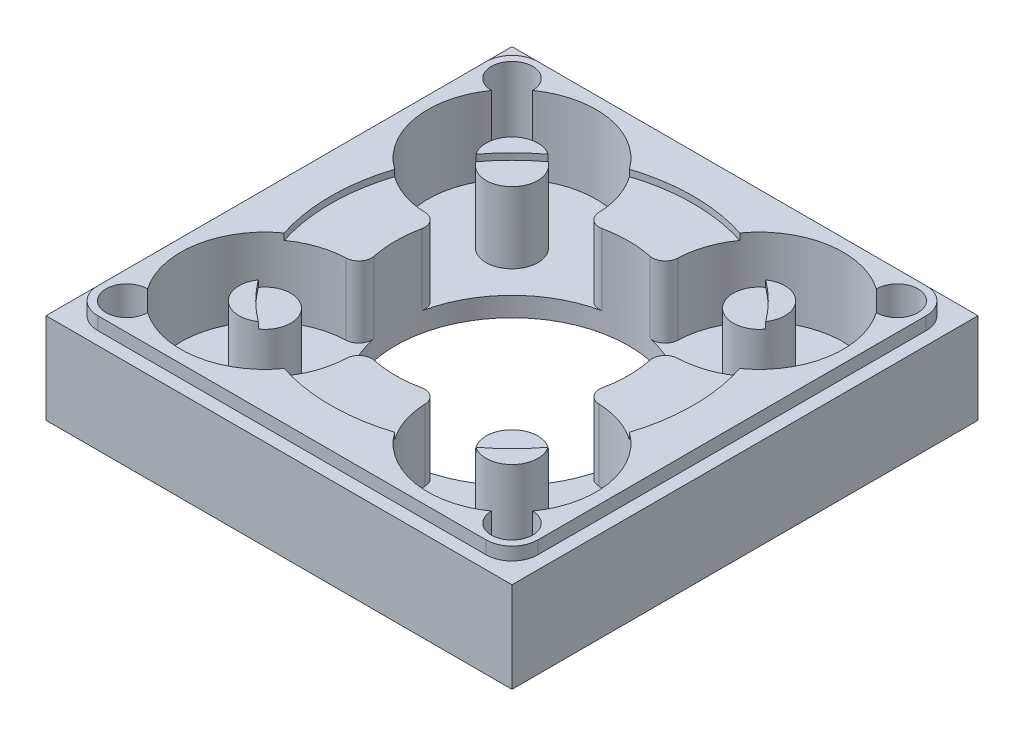
SolidWorks part; units mm, degrees
material "6061 Alloy"
ref_plane "Front Plane" through (0, 0, 0) normal (0, 0, 1) x (1, 0, 0)
ref_plane "Top Plane" through (0, 0, 0) normal (0, 1, 0) x (1, 0, 0)
ref_plane "Right Plane" through (0, 0, 0) normal (1, 0, 0) x (0, 0, -1)
sketch "Sketch1" plane through (0, 0, 0) normal (0, 1, 0) x (1, 0, 0)
  line L1 (-28.575, -28.575) -> (28.575, -28.575)
  line L2 (-28.575, -28.575) -> (-28.575, 28.575)
  line L3 (-28.575, 28.575) -> (28.575, 28.575)
  line L4 (28.575, -28.575) -> (28.575, 28.575)
  line L5 (-28.575, -28.575) -> (28.575, 28.575) construction
  line L6 (-28.575, 28.575) -> (28.575, -28.575) construction
  circle A0 centre (0, 0) radius 14.2875
  point P0 (0, 0)
  dimension "D2" = 28.575
  dimension "D1" = 57.15
extrude "Stock" add sketch "Sketch1" along normal blind 12.7
sketch "Sketch6" plane through (0, 0, 0) normal (0, -1, 0) x (1, 0, 0)
  line L1 (23.622, -23.622) -> (-23.622, -23.622) construction
  line L2 (23.622, -23.622) -> (23.622, 23.622) construction
  line L3 (23.622, 23.622) -> (-23.622, 23.622) construction
  line L4 (-23.622, -23.622) -> (-23.622, 23.622) construction
  line L5 (23.622, -23.622) -> (-23.622, 23.622) construction
  line L6 (23.622, 23.622) -> (-23.622, -23.622) construction
  circle A0 centre (-23.622, 23.622) radius 2.54
  circle A1 centre (23.622, 23.622) radius 2.54
  circle A2 centre (23.622, -23.622) radius 2.54
  circle A3 centre (-23.622, -23.622) radius 2.54
  point P0 (0, 0)
  dimension "D2" = 5.08
  dimension "D1" = 47.244
extrude "Mount Holes" cut sketch "Sketch6" against normal through all
sketch "Sketch2" plane through (0, 12.7, 0) normal (0, 1, 0) x (1, 0, 0)
  line L1 (-23.8125, -26.9875) -> (23.8125, -26.9875)
  line L2 (-26.9875, -23.8125) -> (-26.9875, 23.8125)
  line L3 (-23.8125, 26.9875) -> (23.8125, 26.9875)
  line L4 (26.9875, -23.8125) -> (26.9875, 23.8125)
  line L5 (-26.9875, -26.9875) -> (26.9875, 26.9875) construction
  line L6 (-26.9875, 26.9875) -> (26.9875, -26.9875) construction
  line L7 (28.575, 28.575) -> (-28.575, 28.575)
  line L8 (28.575, 28.575) -> (28.575, -28.575)
  line L9 (28.575, -28.575) -> (-28.575, -28.575)
  line L10 (-28.575, 28.575) -> (-28.575, -28.575)
  line L11 (28.575, 28.575) -> (-28.575, -28.575) construction
  line L12 (28.575, -28.575) -> (-28.575, 28.575) construction
  arc A0 (23.8125, 26.9875) -> (26.9875, 23.8125) centre (23.8125, 23.8125) cw
  arc A1 (23.8125, -26.9875) -> (26.9875, -23.8125) centre (23.8125, -23.8125) ccw
  arc A2 (-23.8125, -26.9875) -> (-26.9875, -23.8125) centre (-23.8125, -23.8125) cw
  arc A3 (-26.9875, 23.8125) -> (-23.8125, 26.9875) centre (-23.8125, 23.8125) cw
  point P0 (0, 0)
  point P18 (0, 0)
  dimension "D2" = 3.175
  dimension "D1" = 53.975
extrude "Lip" cut sketch "Sketch2" against normal blind 1.5875
sketch "Sketch4" plane through (0, 12.7, 0) normal (0, 1, 0) x (1, 0, 0)
  line L0 (0, 0) -> (15.1542, 15.1542) construction
  line L1 (0, 0) -> (15.1542, 15.1542) construction
  line L2 (28.575, -28.575) -> (28.575, 28.575) construction
  line L3 (0, 0) -> (15.1542, -15.1542) construction
  circle A0 centre (15.1542, 15.1542) radius 10.3187
  circle A1 centre (15.1542, -15.1542) radius 10.3187
  circle A2 centre (15.1542, -15.1542) radius 3.175
  circle A3 centre (-15.1542, -15.1542) radius 10.3187
  circle A4 centre (15.1542, 15.1542) radius 3.175
  circle A5 centre (-15.1542, -15.1542) radius 3.175
  circle A6 centre (-15.1542, 15.1542) radius 10.3187
  circle A7 centre (-15.1542, 15.1542) radius 3.175
  point P15 (0, 0)
  point P23 (0, 0)
  dimension "D3" = 20.6375
  dimension "D5" = 6.35
  dimension "D1" = 21.4312
  dimension "D2" = 45
  dimension "D6" = 90
  dimension "D4" = 4
extrude "Bearing Cuts" cut sketch "Sketch4" against normal blind 9.525
sketch "Sketch5" plane through (0, 12.7, 0) normal (0, 1, 0) x (1, 0, 0)
  circle A0 centre (0, 0) radius 22.225
  dimension "D1" = 44.45
extrude "Inner Race" cut sketch "Sketch5" against normal blind 0.7937
sketch "Sketch8" plane through (0, 0, 0) normal (0, -1, 0) x (1, 0, 0)
  circle A0 centre (0, 0) radius 22.225
  dimension "D1" = 44.45
extrude "Outer Race" cut sketch "Sketch8" against normal blind 0.7937
fillet "Fillet1" radius 1.5875 8 edges at (13.3887, 7.5406, -4.9876) (4.9876, 7.5406, -13.3887) (13.3887, 7.5406, 4.9876) (4.9876, 7.5406, 13.3887) (-4.9876, 7.5406, -13.3887) (-13.3887, 7.5406, -4.9876) (-13.3887, 7.5406, 4.9876) (-4.9876, 7.5406, 13.3887)
